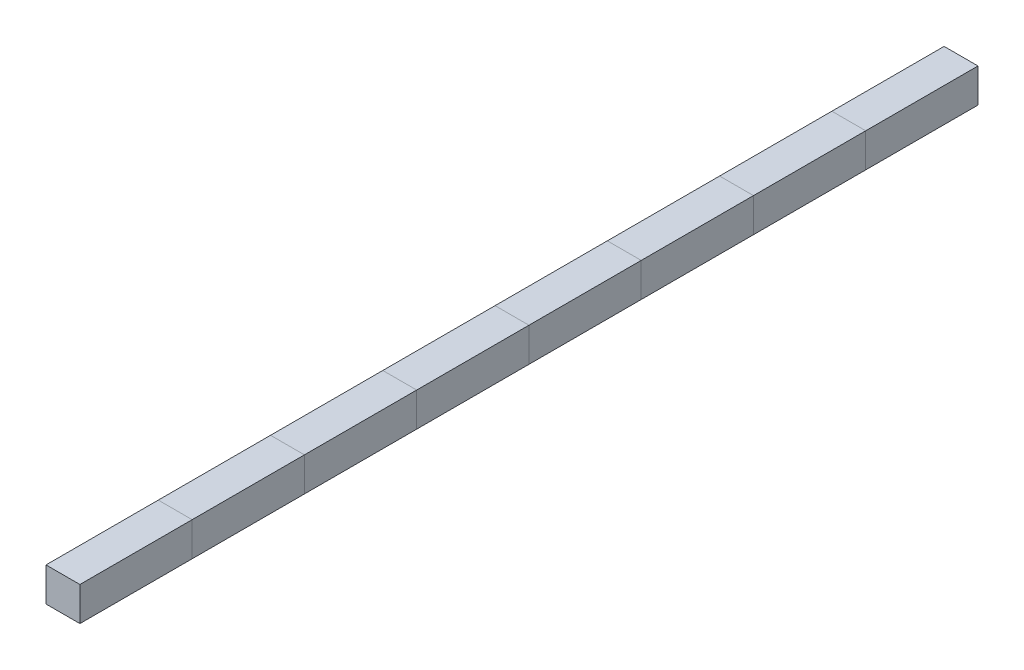
SolidWorks part; units mm, degrees
ref_plane "Front Plane" through (0, 0, 0) normal (0, 0, 1) x (1, 0, 0)
ref_plane "Top Plane" through (0, 0, 0) normal (0, 1, 0) x (1, 0, 0)
ref_plane "Right Plane" through (0, 0, 0) normal (1, 0, 0) x (0, 0, -1)
sketch "Sketch1" plane through (0, 0, 0) normal (0, 0, 1) x (1, 0, 0)
  line L1 (-10, -10) -> (10, -10)
  line L2 (-10, -10) -> (-10, 10)
  line L3 (-10, 10) -> (10, 10)
  line L4 (10, -10) -> (10, 10)
  line L5 (-10, -10) -> (10, 10) construction
  line L6 (-10, 10) -> (10, -10) construction
  point P0 (0, 0)
  dimension "D1" = 20
extrude "Boss-Extrude1" add sketch "Sketch1" along normal blind 66.25
pattern_linear "LPattern1" count 8 spacing 66.25 along (0, 0, -1) of bodies 101
